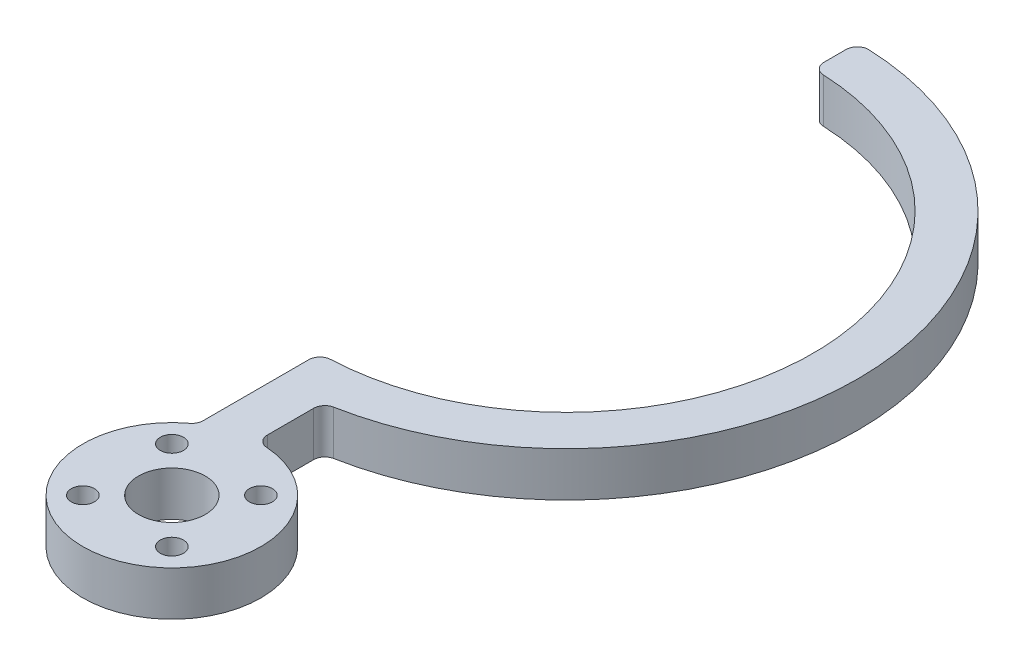
SolidWorks part; units mm, degrees
ref_plane "Front Plane" through (0, 0, 0) normal (0, 0, 1) x (1, 0, 0)
ref_plane "Top Plane" through (0, 0, 0) normal (0, 1, 0) x (1, 0, 0)
ref_plane "Right Plane" through (0, 0, 0) normal (1, 0, 0) x (0, 0, -1)
sketch "Sketch1" plane through (0, 0, 0) normal (0, 1, 0) x (1, 0, 0)
  line L0 (0, 52.33) -> (0, 44.33)
  line L1 (0, -44.33) -> (0, -54.33)
  line L2 (0, -54.33) -> (0, -66.33)
  line L3 (8, -51.7149) -> (8, -63.7149)
  line L8 (16.7963, -87.6951) -> (0.7963, -87.6951) construction
  line L13 (16.7963, -87.6951) -> (16.7963, -71.6951) construction
  line L21 (16.7963, -71.6951) -> (0.7963, -71.6951) construction
  line L22 (0.7963, -87.6951) -> (0.7963, -71.6951) construction
  line L23 (16.7963, -87.6951) -> (0.7963, -71.6951) construction
  line L24 (16.7963, -71.6951) -> (0.7963, -87.6951) construction
  arc A0 (0, -44.33) -> (0, 44.33) centre (0, 0) ccw
  arc A1 (8, -51.7149) -> (0, 52.33) centre (0, 0) ccw
  arc A7 (0, -66.33) -> (22.907, -87.2375) centre (8.7963, -79.6951) ccw
  circle A8 centre (0.7963, -71.6951) radius 2.075
  circle A9 centre (16.7963, -71.6951) radius 2.075
  circle A10 centre (16.7963, -87.6951) radius 2.075
  circle A11 centre (0.7963, -87.6951) radius 2.075
  arc A12 (0, -66.33) -> (8, -63.7149) centre (8.7963, -79.6951) ccw
  circle A13 centre (8.7963, -79.6951) radius 6.0032
  dimension "D1" = 88.66
  dimension "D8" = 4.15
  dimension "D6" = 16
  dimension "D2" = 8
  dimension "D3" = 8
  dimension "D4" = 12
  dimension "D9" = 10
  dimension "D7" = 16
  dimension "D5" = 12
extrude "Boss-Extrude2" add sketch "Sketch1" along normal blind 8 contours A7 A12 L3 A1 L0 A0 L1 L2 A8 A9 A10 A11
fillet "Fillet1" radius 2 6 edges at (0, 4, -44.33) (0, 4, -52.33) (8, 4, 63.7149) (8, 4, 51.7149) (0, 4, 66.33) (0, 4, 44.33)
equation "\"innerSmall\"= 2.9in"
equation "\"thick\"= 8mm"
equation "\"D1@Sketch1\"=\"innerSmall\"+15"
equation "\"D2@Sketch1\"=\"thick\""
equation "\"D3@Sketch1\"=\"thick\""
equation "\"D7@Sketch1\"=16mm"
